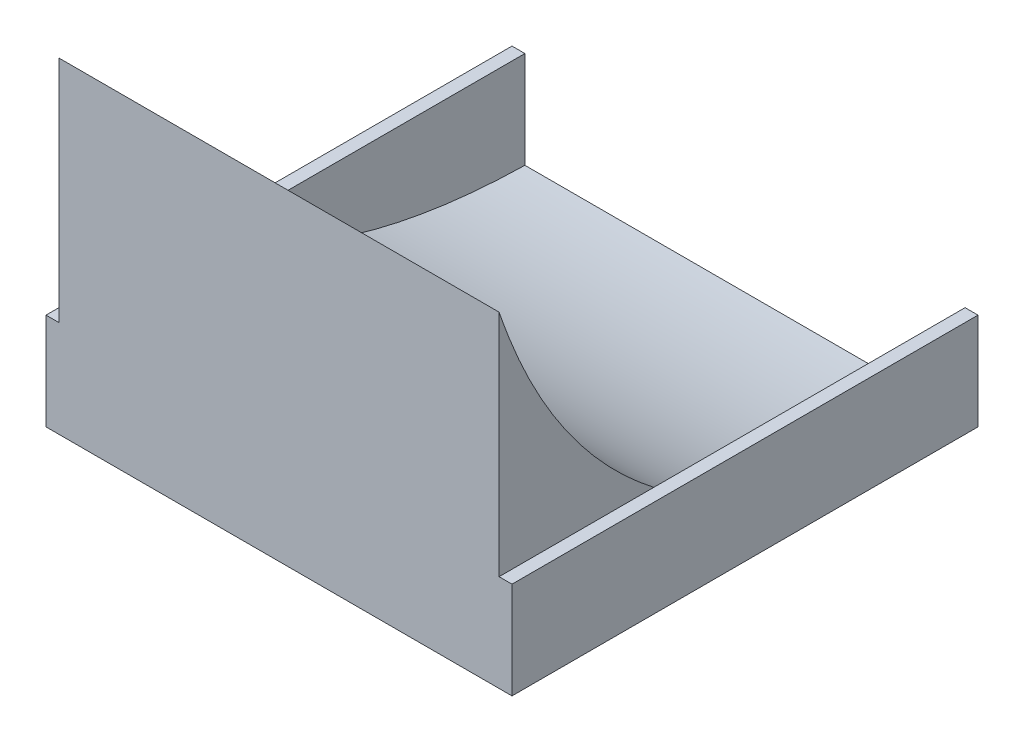
SolidWorks part; units mm, degrees
ref_plane "Front Plane" through (0, 0, 0) normal (0, 0, 1) x (1, 0, 0)
ref_plane "Top Plane" through (0, 0, 0) normal (0, 1, 0) x (1, 0, 0)
ref_plane "Right Plane" through (0, 0, 0) normal (1, 0, 0) x (0, 0, -1)
sketch "Sketch1" plane through (0, 0, 0) normal (1, 0, 0) x (0, 0, -1)
  line L0 (0, 0) -> (72.2, 0)
  line L2 (0, 50.5) -> (0, 0)
  spline S0 degree 2 poles (0, 50.5) (16.7493, 1.1442) (72.2, 0) knots 0 0 0 1 1 1
  dimension "D1" = 72.2
  dimension "D2" = 50.5
extrude "Boss-Extrude1" add sketch "Sketch1" along normal blind 68.2
sketch "Sketch2" plane through (0, 0, 0) normal (-1, 0, 0) x (0, 0, 1)
  line L1 (0, 0) -> (-72.2, 0)
  line L2 (0, 0) -> (0, 15)
  line L3 (0, 15) -> (-72.2, 15)
  line L4 (-72.2, 0) -> (-72.2, 15)
  dimension "D1" = 72.2
  dimension "D2" = 15
extrude "Boss-Extrude2" add sketch "Sketch2" along normal blind 2
sketch "Sketch3" plane through (68.2, 0, 0) normal (1, 0, 0) x (0, 0, -1)
  line L1 (0, 0) -> (72.2, 0)
  line L2 (0, 0) -> (0, 15)
  line L3 (0, 15) -> (72.2, 15)
  line L4 (72.2, 0) -> (72.2, 15)
extrude "Boss-Extrude3" add sketch "Sketch3" along normal blind 2
